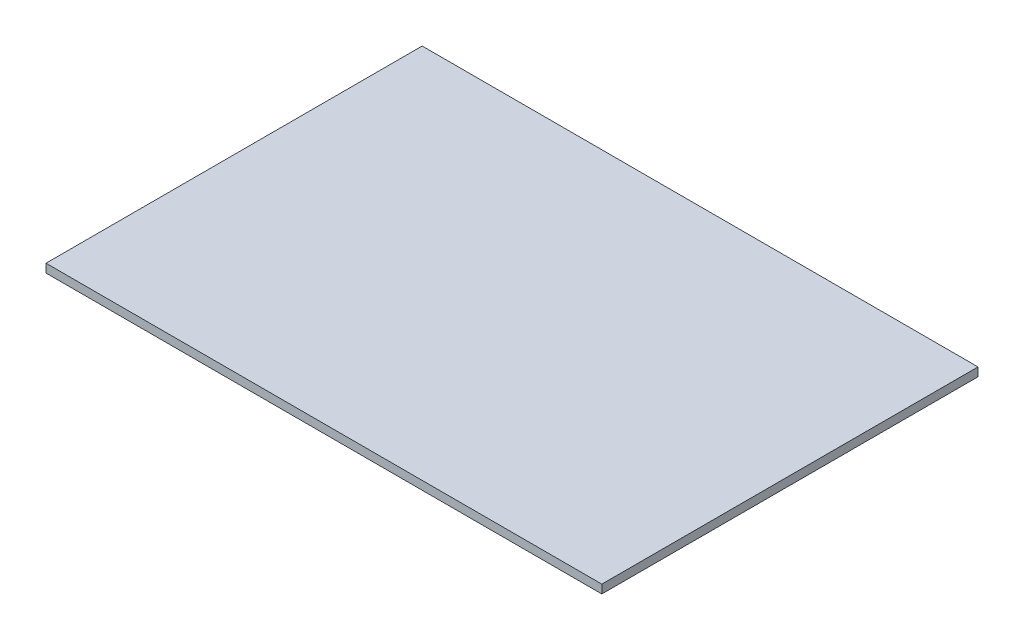
SolidWorks part; units mm, degrees
ref_plane "Front Plane" through (0, 0, 0) normal (0, 0, 1) x (1, 0, 0)
ref_plane "Top Plane" through (0, 0, 0) normal (0, 1, 0) x (1, 0, 0)
ref_plane "Right Plane" through (0, 0, 0) normal (1, 0, 0) x (0, 0, -1)
sketch "Sketch1" plane through (0, 0, 0) normal (0, 1, 0) x (1, 0, 0)
  line L1 (-32.9683, 21.6597) -> (121.7209, 21.6597)
  line L2 (-32.9683, 21.6597) -> (-32.9683, -83.0312)
  line L3 (-32.9683, -83.0312) -> (121.7209, -83.0312)
  line L4 (121.7209, 21.6597) -> (121.7209, -83.0312)
extrude "Boss-Extrude1" add sketch "Sketch1" along normal blind 2.3817
